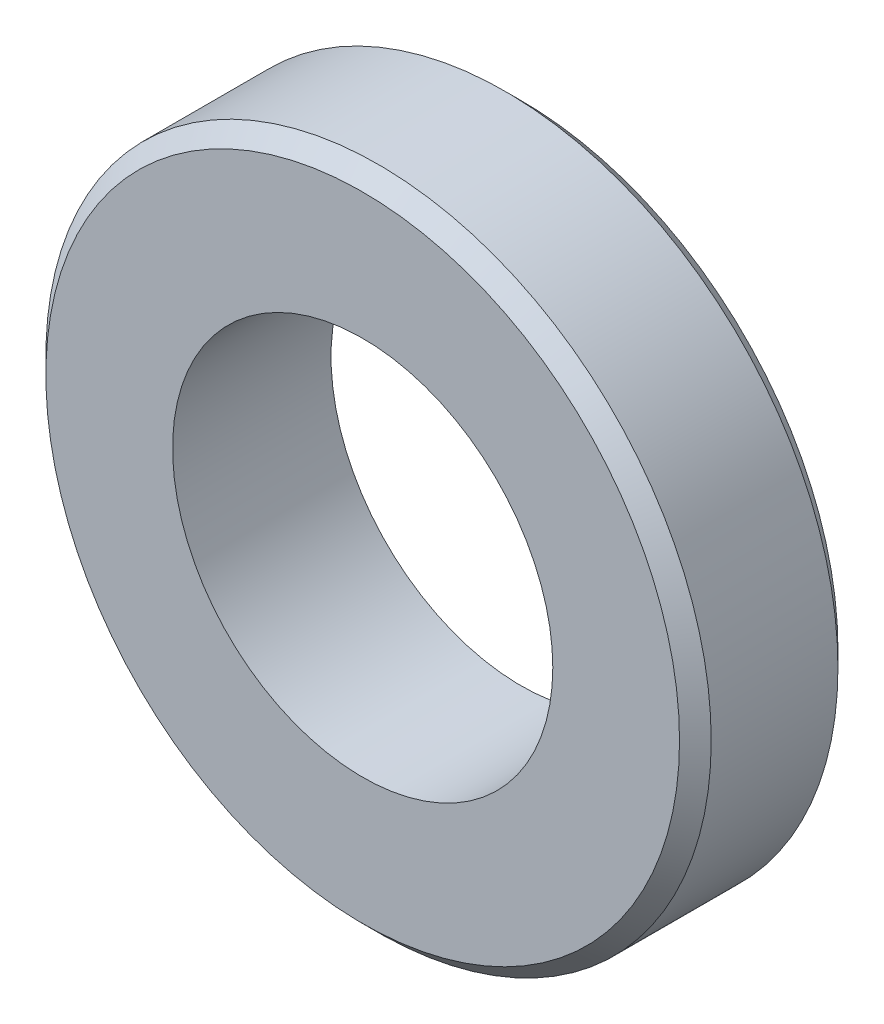
SolidWorks part; units mm, degrees
ref_plane "前视基准面" through (0, 0, 0) normal (0, 0, 1) x (1, 0, 0)
ref_plane "上视基准面" through (0, 0, 0) normal (0, 1, 0) x (1, 0, 0)
ref_plane "右视基准面" through (0, 0, 0) normal (1, 0, 0) x (0, 0, -1)
other "Configuration Table"
sketch "草图1" plane through (0, 0, 0) normal (0, 0, 1) x (1, 0, 0)
  circle A0 centre (0, 0) radius 6
  circle A1 centre (0, 0) radius 10.5
  dimension "D1" = 12
  dimension "D2" = 21
extrude "凸台-拉伸1" add sketch "草图1" along normal blind 5
chamfer "倒角1" distance 0.5 angle 45 2 edges at (10.5, 0, 0) (10.5, 0, 5)
